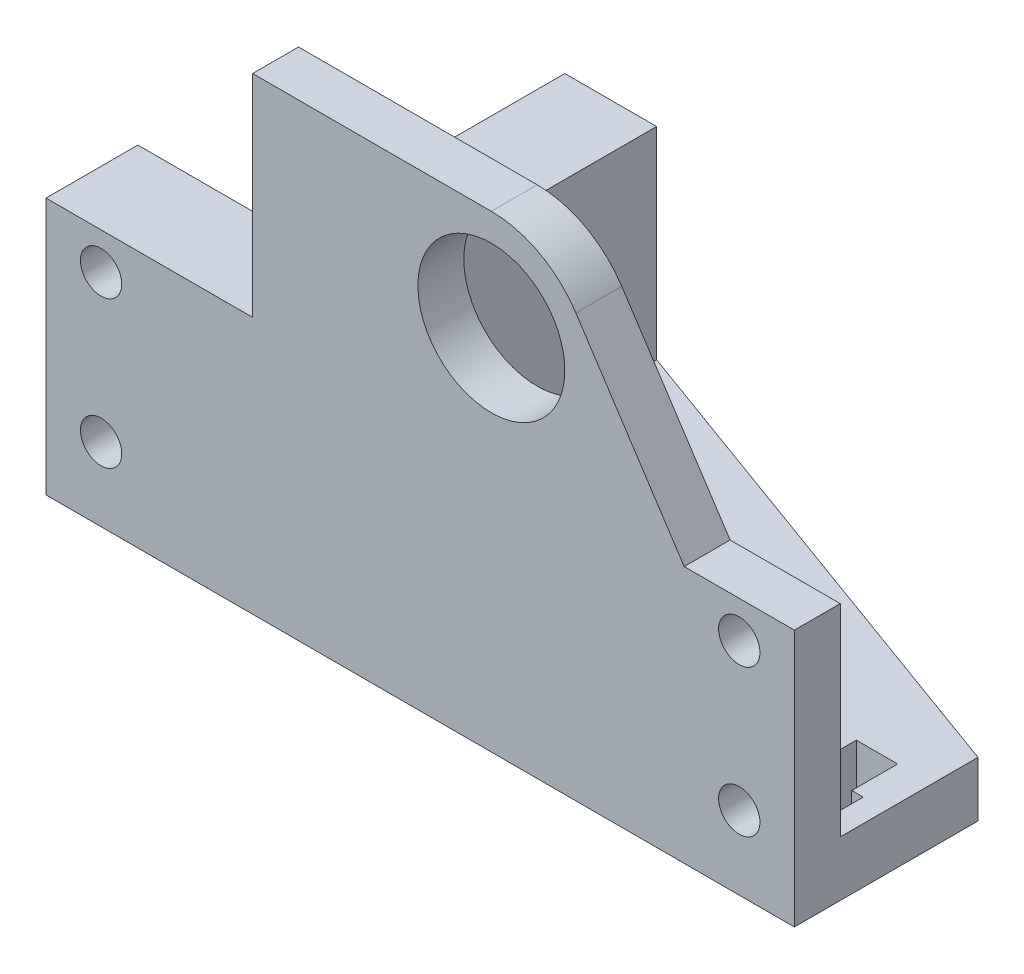
SolidWorks part; units mm, degrees
material "Printed PLA"
ref_plane "Front Plane" through (0, 0, 0) normal (0, 0, 1) x (1, 0, 0)
ref_plane "Top Plane" through (0, 0, 0) normal (0, 1, 0) x (1, 0, 0)
ref_plane "Right Plane" through (0, 0, 0) normal (1, 0, 0) x (0, 0, -1)
sketch "Sketch2" plane through (0, 0, 0) normal (0, 1, 0) x (1, 0, 0)
  line L0 (-16.5, 0) -> (0, 0)
  line L1 (0, 0) -> (0, 30)
  line L2 (0, 30) -> (10, 30)
  line L3 (10, 30) -> (10, -10)
  line L4 (10, -10) -> (-16.5, -10)
  line L5 (-16.5, -10) -> (-16.5, 0)
  dimension "D1" = 10
  dimension "D2" = 16.5
  dimension "D3" = 30
extrude "Boss-Extrude1" add sketch "Sketch2" along normal blind 28
sketch "Sketch3" plane through (0, 0, 0) normal (0, 1, 0) x (1, 0, 0)
  line L1 (10, -10) -> (53, -10)
  line L2 (10, -10) -> (10, -5)
  line L3 (10, -5) -> (53, -5)
  line L4 (53, -10) -> (53, -5)
  dimension "D1" = 5
  dimension "D2" = 43
extrude "Boss-Extrude2" add sketch "Sketch3" along normal blind 51
sketch "Sketch4" plane through (0, 0, 5) normal (0, 0, -1) x (-1, 0, 0)
  line L0 (-47.5, 55.5) -> (-47.5, 24.5) construction
  line L1 (-47.5, 24.5) -> (-16.5, 24.5) construction
  line L2 (-16.5, 24.5) -> (-16.5, 55.5) construction
  line L3 (-16.5, 55.5) -> (-47.5, 55.5) construction
  line L4 (-47.5, 55.5) -> (-16.5, 24.5) construction
  line L5 (-10, 28) -> (-10, 0) construction
  line L6 (-53, 0) -> (-10, 0) construction
  circle A0 centre (-32, 40) radius 8
  circle A1 centre (-16.5, 55.5) radius 1.75 construction
  circle A2 centre (-16.5, 24.5) radius 1.75 construction
  circle A3 centre (-47.5, 24.5) radius 1.75 construction
  circle A4 centre (-47.5, 55.5) radius 1.75 construction
  dimension "D2" = 16
  dimension "D3" = 3.5
  dimension "D1" = 31
  dimension "D4" = 22
  dimension "D5" = 40
extrude "Cut-Extrude1" cut sketch "Sketch4" against normal through all
sketch "Sketch6" plane through (-16.5, 0, 0) normal (-1, 0, 0) x (0, 0, 1)
  line L0 (10, 28) -> (10, 0)
  line L1 (10, 0) -> (18, 0)
  line L2 (18, 0) -> (18, 12)
  line L3 (18, 20) -> (18, 28)
  line L4 (18, 28) -> (10, 28)
  line L5 (18, 16) -> (0, 16) construction
  line L8 (0, 28) -> (0, 0) construction
  arc A0 (18, 12) -> (18, 20) centre (18, 16) cw
  dimension "D1" = 4
  dimension "D2" = 18
  dimension "D3" = 12
extrude "Boss-Extrude3" add sketch "Sketch6" against normal blind 12
sketch "Sketch7" plane through (53, 0, 0) normal (1, 0, 0) x (0, 0, -1)
  line L0 (-18, 12) -> (-18, 0)
  line L1 (-5, 28) -> (-18, 28)
  line L2 (-5, 28) -> (-5, 0)
  line L3 (-5, 0) -> (-18, 0)
  line L4 (-18, 28) -> (-18, 20)
  arc A0 (-18, 12) -> (-18, 20) centre (-18, 16) ccw
  arc A1 (-18, 12) -> (-18, 20) centre (-18, 16) ccw construction
extrude "Boss-Extrude4" add sketch "Sketch7" along normal blind 12
sketch "Sketch5" plane through (0, 0, 18) normal (0, 0, 1) x (1, 0, 0)
  line L0 (-10.5, 24) -> (-10.5, 8) construction
  line L1 (-16.5, 16) -> (-10.5, 16) construction
  line L4 (-16.5, 20) -> (-16.5, 12) construction
  line L5 (-4.5, 0) -> (53, 0) construction
  line L6 (24.25, 0) -> (24.25, 20) construction
  line L7 (65, 16) -> (59, 16) construction
  line L8 (59, 24) -> (59, 8) construction
  circle A0 centre (-10.5, 24) radius 2.25
  circle A1 centre (-10.5, 8) radius 2.25
  circle A2 centre (59, 8) radius 2.25
  circle A3 centre (59, 24) radius 2.25
  dimension "D1" = 4.5
  dimension "D2" = 16
  dimension "D3" = 6
extrude "Cut-Extrude2" cut sketch "Sketch5" against normal through all
sketch "Sketch8" plane through (0, 0, 0) normal (0, 1, 0) x (1, 0, 0)
  line L1 (10, 30) -> (65, 30)
  line L2 (10, 30) -> (10, -5)
  line L3 (10, -5) -> (65, -5)
  line L4 (65, 30) -> (65, -5)
extrude "Boss-Extrude5" add sketch "Sketch8" along normal blind 6
sketch "Sketch9" plane through (0, 6, 0) normal (0, 1, 0) x (-1, 0, 0)
  line L0 (-53, 5) -> (-65, 5) construction
  line L1 (-62.5, 5) -> (-55.5, 5)
  line L2 (-62.5, 5) -> (-62.5, 0)
  line L3 (-62.5, 0) -> (-61.25, 0)
  line L4 (-55.5, 5) -> (-55.5, 0)
  line L5 (-56.75, 0) -> (-55.5, 0)
  line L6 (-59, -5) -> (-59, 18) construction
  line L7 (-61.25, 0) -> (-61.25, -5)
  line L8 (-61.25, -5) -> (-56.75, -5)
  line L9 (-56.75, 0) -> (-56.75, -5)
  line L10 (-65, 18) -> (-53, 18) construction
  dimension "D1" = 4.5
  dimension "D2" = 7
  dimension "D3" = 5
  dimension "D4" = 5
extrude "Cut-Extrude3" cut sketch "Sketch9" against normal through all
sketch "Sketch10" plane through (10, 0, 0) normal (-1, 0, 0) x (0, 0, 1)
  line L0 (-30, 0) -> (5, 51)
  line L1 (5, 51) -> (10, 51)
  line L2 (10, 51) -> (10, 29.1429) construction
  line L3 (10, 51) -> (10, 28) construction
  line L4 (10, 29.1429) -> (5, 29.1429) construction
  line L5 (5, 51) -> (5, 28) construction
  line L6 (5, 29.1429) -> (-15, 0) construction
  line L7 (-30, 0) -> (0, 0) construction
  line L8 (-15, 0) -> (-30, 0)
  line L9 (5, 29.1429) -> (10, 36.4286) construction
  line L10 (10, 36.4286) -> (10, 51)
  line L11 (-15, 0) -> (10, 0)
  line L12 (10, 0) -> (10, 36.4286)
extrude "Boss-Extrude6" add sketch "Sketch10" along normal blind 4
sketch "Sketch11" plane through (10, 0, 0) normal (1, 0, 0) x (0, 0, -1)
  line L0 (24, 10.5) -> (12, 10.5) construction
  line L1 (-5, 6) -> (30, 6) construction
  line L2 (30, 6) -> (30, 28) construction
  circle A0 centre (12, 10.5) radius 2.25 construction
  circle A1 centre (24, 10.5) radius 2.25
  point P4 (12.5, 6)
  dimension "D1" = 4.5
  dimension "D2" = 12
  dimension "D3" = 4.5
  dimension "D4" = 6
extrude "Cut-Extrude4" cut sketch "Sketch11" against normal through all
sketch "Sketch12" plane through (0, 6, 0) normal (0, 1, 0) x (-1, 0, 0)
  line L0 (-38, -8) -> (-18, -8) construction
  line L1 (-53, 5) -> (-10, 5) construction
  line L2 (-10, -30) -> (-10, 5) construction
  circle A0 centre (-18, -8) radius 2.25
  circle A1 centre (-38, -8) radius 2.25
  dimension "D1" = 4.5
  dimension "D4" = 8
  dimension "D2" = 20
  dimension "D3" = 13
extrude "Cut-Extrude5" cut sketch "Sketch12" against normal up to next
sketch "Sketch13" plane through (0, 6, 0) normal (0, 1, 0) x (-1, 0, 0)
  line L0 (-10, -30) -> (-65, -10)
  line L1 (-65, 5) -> (-65, -30) construction
  line L2 (-65, -10) -> (-65, -30)
  line L3 (-65, -30) -> (-10, -30) construction
  line L4 (-65, -30) -> (-10, -30)
  line L5 (-10, -10.7843) -> (-10, -30) construction
  line L6 (-10, -30) -> (-10, 5) construction
  dimension "D1" = 20
extrude "Cut-Extrude6" cut sketch "Sketch13" against normal through all
sketch "Sketch14" plane through (0, 0, 10) normal (0, 0, 1) x (1, 0, 0)
  line L0 (32, 51) -> (32, 40) construction
  line L1 (6, 51) -> (53, 51) construction
  line L2 (41.204, 46.0237) -> (53, 28)
  line L3 (53, 28) -> (53, 51)
  line L4 (53, 51) -> (32, 51)
  arc A0 (32, 51) -> (41.204, 46.0237) centre (32, 40) cw
  circle A1 centre (32, 40) radius 8 construction
extrude "Cut-Extrude7" cut sketch "Sketch14" against normal through all
sketch "Sketch15" plane through (-16.5, 0, 0) normal (-1, 0, 0) x (0, 0, 1)
  line L1 (10, 28) -> (18, 28)
  line L2 (10, 28) -> (10, 0)
  line L3 (10, 0) -> (18, 0)
  line L4 (18, 28) -> (18, 0)
extrude "Cut-Extrude8" cut sketch "Sketch15" against normal through all
